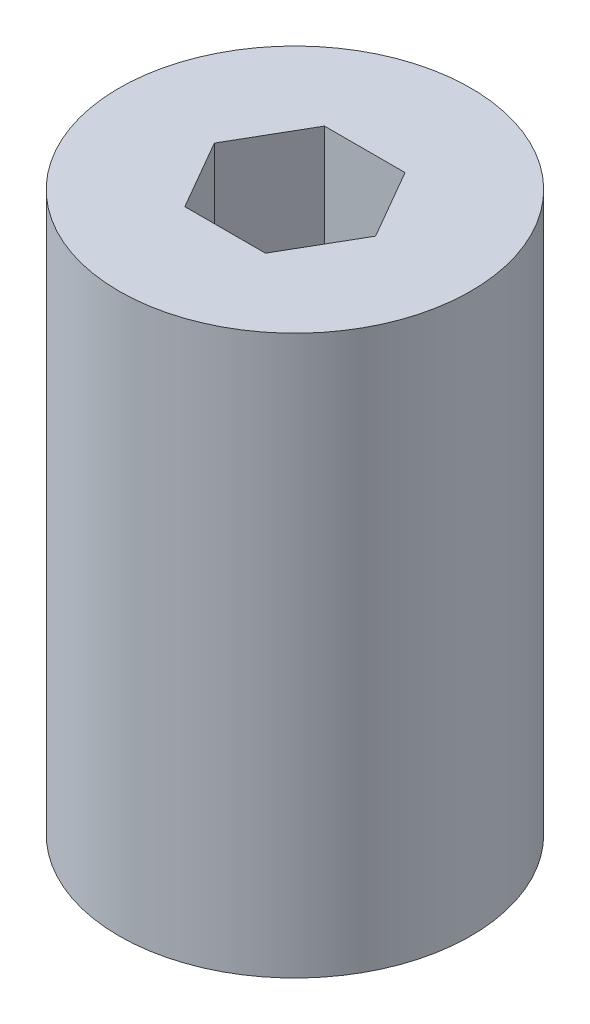
SolidWorks part; units mm, degrees
ref_plane "Front Plane" through (0, 0, 0) normal (0, 0, 1) x (1, 0, 0)
ref_plane "Top Plane" through (0, 0, 0) normal (0, 1, 0) x (1, 0, 0)
ref_plane "Right Plane" through (0, 0, 0) normal (1, 0, 0) x (0, 0, -1)
sketch "Sketch2" plane through (0, 0, 0) normal (0, 1, 0) x (1, 0, 0)
  circle A0 centre (0, 0) radius 16.002
  dimension "D1" = 32.004
extrude "Boss-Extrude1" add sketch "Sketch2" along normal blind 50.8 contours A0
sketch "Sketch3" plane through (0, 50.8, 0) normal (0, 1, 0) x (1, 0, 0)
  line L1 (7.3323, 0) -> (3.6662, 6.35)
  line L2 (3.6662, 6.35) -> (-3.6662, 6.35)
  line L3 (-3.6662, 6.35) -> (-7.3323, 0)
  line L4 (-7.3323, 0) -> (-3.6662, -6.35)
  line L5 (-3.6662, -6.35) -> (3.6662, -6.35)
  line L6 (3.6662, -6.35) -> (7.3323, 0)
  circle A0 centre (0, 0) radius 6.35 construction
extrude "Cut-Extrude1" cut sketch "Sketch3" against normal through all
